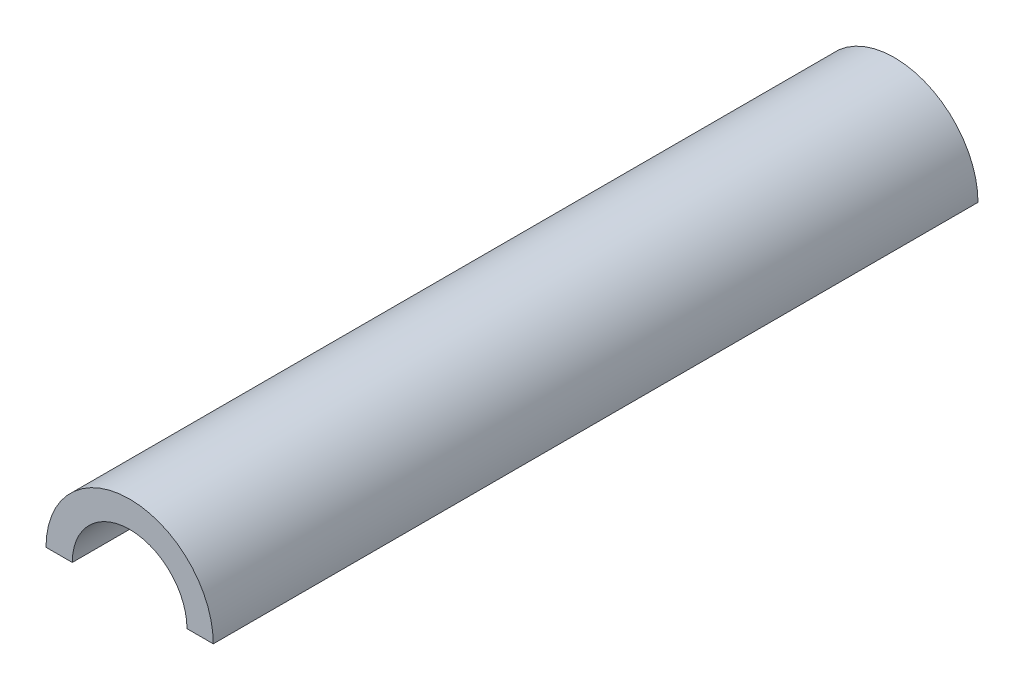
SolidWorks part; units mm, degrees
ref_plane "Front Plane" through (0, 0, 0) normal (0, 0, 1) x (1, 0, 0)
ref_plane "Top Plane" through (0, 0, 0) normal (0, 1, 0) x (1, 0, 0)
ref_plane "Right Plane" through (0, 0, 0) normal (1, 0, 0) x (0, 0, -1)
sketch "Sketch1" plane through (0, 0, 0) normal (0, 0, 1) x (1, 0, 0)
  line L5 (17.5, 0) -> (12, 0)
  line L6 (-12, 0) -> (-17.5, 0)
  arc A0 (12, 0) -> (-12, 0) centre (0, 0) ccw
  arc A1 (17.5, 0) -> (-17.5, 0) centre (0, 0) ccw
  dimension "D1" = 24
  dimension "D2" = 35
extrude "Boss-Extrude1" add sketch "Sketch1" along normal mid plane 160
ref_plane "Plane1" through (0, 17.5, 0) normal (0, 1, 0) x (1, 0, 0)
sketch "Sketch4" plane through (0, 0, 0) normal (0, 0, 1) x (1, 0, 0)
  line L0 (0, 0) -> (12.3744, 12.3744) construction
  line L1 (0, -9.625) -> (0, 9.625) construction
  line L2 (0, 0) -> (-12.3744, 12.3744) construction
  line L3 (19.25, 0) -> (-19.25, 0) construction
  line L6 (10.0699, 14.3125) -> (0, 0)
  line L7 (0, 0) -> (-10.0699, 14.3125)
  arc A0 (10.0699, 14.3125) -> (-10.0699, 14.3125) centre (0, 0) ccw
  dimension "D1" = 35
  dimension "D2" = 90
  dimension "D3" = 3
  dimension "D4" = 3
  dimension "D5" = 10.0699
